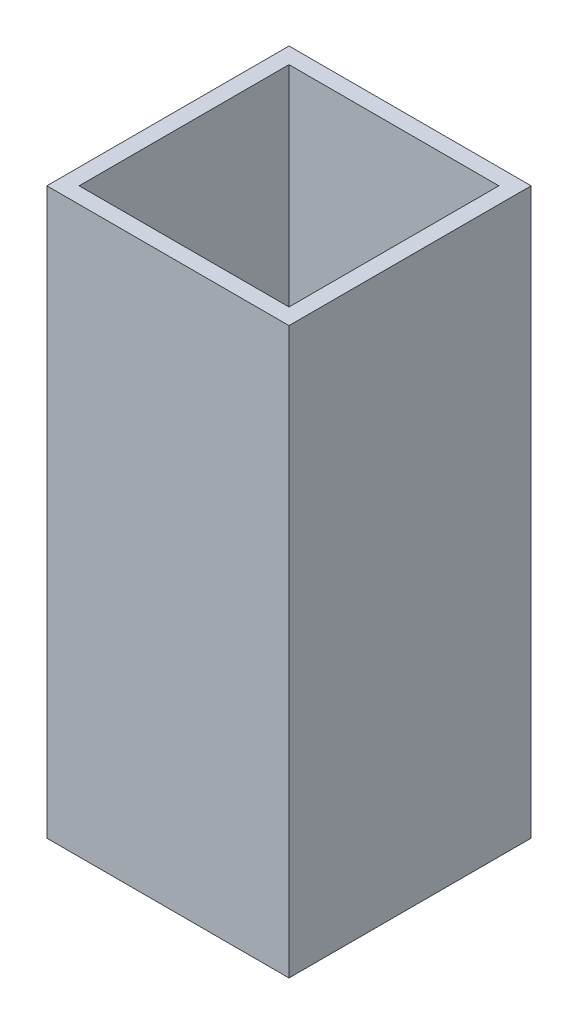
SolidWorks part; units mm, degrees
ref_plane "Front Plane" through (0, 0, 0) normal (0, 0, 1) x (1, 0, 0)
ref_plane "Top Plane" through (0, 0, 0) normal (0, 1, 0) x (1, 0, 0)
ref_plane "Right Plane" through (0, 0, 0) normal (1, 0, 0) x (0, 0, -1)
sketch "Sketch1" plane through (0, 0, 0) normal (0, 1, 0) x (1, 0, 0)
  line L0 (-13, 13) -> (13, 13)
  line L1 (-15, -15) -> (15, -15)
  line L2 (-15, -15) -> (-15, 15)
  line L3 (-15, 15) -> (15, 15)
  line L4 (15, -15) -> (15, 15)
  line L5 (-15, -15) -> (15, 15) construction
  line L6 (-15, 15) -> (15, -15) construction
  line L7 (13, -13) -> (13, 13)
  line L8 (-13, -13) -> (13, -13)
  line L9 (-13, -13) -> (-13, 13)
  point P0 (0, 0)
  dimension "D1" = 30
  dimension "D2" = 2
extrude "Boss-Extrude1" add sketch "Sketch1" along normal blind 70
